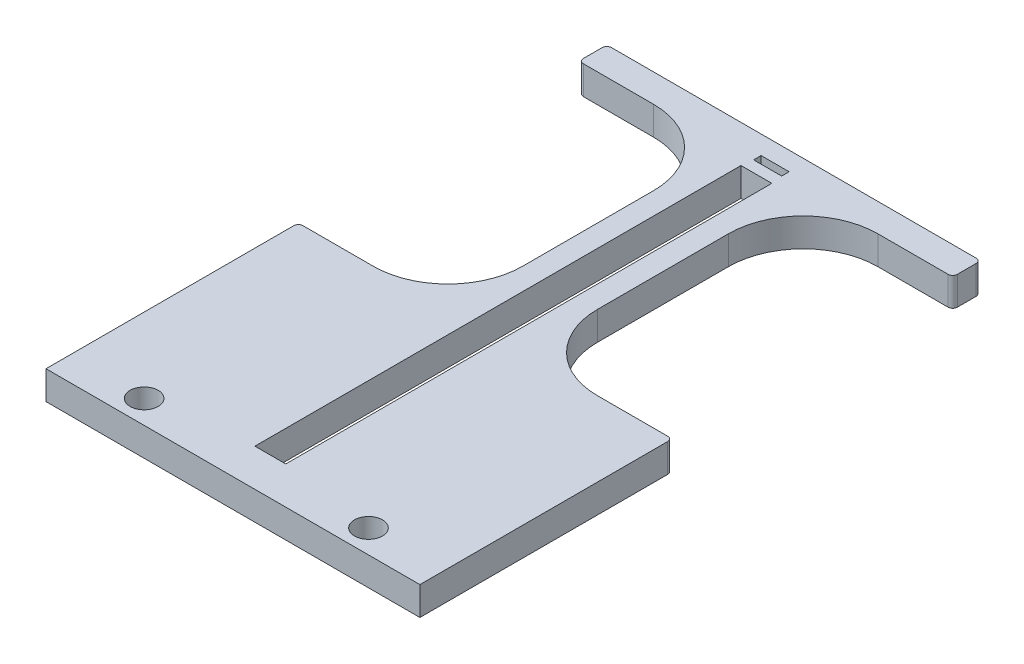
SolidWorks part; units mm, degrees
ref_plane "Front Plane" through (0, 0, 0) normal (0, 0, 1) x (1, 0, 0)
ref_plane "Top Plane" through (0, 0, 0) normal (0, 1, 0) x (1, 0, 0)
ref_plane "Right Plane" through (0, 0, 0) normal (1, 0, 0) x (0, 0, -1)
sketch "Sketch1" plane through (0, 0, 0) normal (0, 1, 0) x (1, 0, 0)
  line L1 (0, 0) -> (40, 0)
  line L2 (0, 0) -> (0, 60)
  line L3 (0, 60) -> (40, 60)
  line L4 (40, 0) -> (40, 60)
  dimension "D1" = 40
  dimension "D2" = 60
extrude "Boss-Extrude1" add sketch "Sketch1" along normal blind 3.05
sketch "Sketch4" plane through (0, 3.05, 0) normal (0, 1, 0) x (1, 0, 0)
  line L0 (20, 60) -> (20, 58)
  line L1 (0, 60) -> (40, 60) construction
  line L3 (21.5, 58) -> (18.5, 58)
  line L4 (18.5, 58) -> (18.5, 57.2)
  line L5 (18.5, 57.2) -> (21.5, 57.2)
  line L6 (21.5, 57.2) -> (21.5, 58)
  line L7 (20, 57.2) -> (20, 56)
  line L9 (21.65, 56) -> (18.35, 56)
  line L10 (18.35, 56) -> (18.35, 4)
  line L11 (18.35, 4) -> (21.65, 4)
  line L12 (21.65, 4) -> (21.65, 56)
  point P10 (20, 58)
  point P22 (20, 56)
  dimension "D1" = 2
  dimension "D2" = 0.8
  dimension "D3" = 1.2
  dimension "D4" = 3
  dimension "D5" = 52
  dimension "D6" = 3.3
extrude "Cut-Extrude1" cut sketch "Sketch4" against normal blind 10 contours L11 L12 L9 L10 | L5 L6 L3 L4
sketch "Sketch5" plane through (0, 3.05, 0) normal (0, 1, 0) x (1, 0, 0)
  line L0 (0, 60) -> (0, 20)
  line L1 (0, 0) -> (0, 60) construction
  line L2 (0, 60) -> (15, 60)
  line L3 (0, 60) -> (40, 60) construction
  line L5 (40, 60) -> (25, 60)
  line L6 (40, 60) -> (40, 20)
  line L7 (40, 0) -> (40, 60) construction
  line L9 (15, 60) -> (15, 20)
  line L10 (15, 20) -> (0, 20)
  line L11 (25, 60) -> (25, 20)
  line L12 (25, 20) -> (40, 20)
  circle A0 centre (7.5, 27.5) radius 7.5
  circle A1 centre (32.5, 27.5) radius 7.5
  line M14 (40, 0) -> (40, 60)
  line M15 (40, 60) -> (0, 60)
  line M16 (0, 60) -> (0, 0)
  dimension "D1" = 40
  dimension "D2" = 15
  dimension "D3" = 40
  dimension "D4" = 15
extrude "Cut-Extrude2" [suppressed] cut sketch "Sketch5" against normal blind 10 contours A0 L9 M15 M16 | A0 | A0 L0 L10 | A1 L6 L11 M15 | A1 | A1 L12 M14
sketch "Sketch6" plane through (0, 3.05, 0) normal (0, 1, 0) x (1, 0, 0)
  line L0 (0, 60) -> (0, 45)
  line L1 (0, 0) -> (0, 60) construction
  line L2 (0, 60) -> (15, 60)
  line L3 (0, 60) -> (40, 60) construction
  line L4 (40, 60) -> (40, 45)
  line L5 (40, 0) -> (40, 60) construction
  line L6 (40, 60) -> (25, 60)
  line L7 (15, 60) -> (0, 45)
  line L8 (25, 60) -> (40, 45)
  dimension "D1" = 15
  dimension "D2" = 15
  dimension "D3" = 15
  dimension "D4" = 15
extrude "Cut-Extrude3" [suppressed] cut sketch "Sketch6" against normal blind 10
sketch "Sketch7" plane through (0, 3.05, 0) normal (0, 1, 0) x (1, 0, 0)
  line L0 (0, 60) -> (0, 57)
  line L1 (0, 0) -> (0, 60) construction
  line L2 (40, 60) -> (40, 57)
  line L3 (0, 57) -> (16, 57)
  line L4 (0, 57) -> (0, 27)
  line L5 (0, 27) -> (16, 27)
  line L6 (16, 57) -> (16, 27)
  line L7 (40, 0) -> (40, 60) construction
  line L9 (40, 57) -> (24, 57)
  line L10 (40, 57) -> (40, 27)
  line L11 (40, 27) -> (24, 27)
  line L12 (24, 57) -> (24, 27)
  circle A0 centre (8, 49) radius 8
  circle A1 centre (8, 35) radius 8
  circle A2 centre (32, 35) radius 8
  circle A3 centre (32, 49) radius 8
  line M18 (40, 0) -> (40, 60)
  line M20 (0, 60) -> (0, 0)
  dimension "D1" = 3
  dimension "D2" = 30
  dimension "D3" = 3
  dimension "D4" = 30
  dimension "D5" = 16
  dimension "D6" = 16
extrude "Cut-Extrude4" cut sketch "Sketch7" against normal blind 10 contours A1 A0 | A0 L3 M20 | A1 L6 A0 | A1 A0 L4 | A1 A0 | A1 L5 M20 | A0 A1 | A3 L12 A2 | A2 A3 | A3 A2 L10 | A2 A3 | A3 A2 | A2 L11 M18 | A3 L9 M18
sketch "Sketch8" plane through (0, 3.05, 0) normal (0, 1, 0) x (1, 0, 0)
  line L0 (0, 0) -> (8, 0)
  line L1 (0, 0) -> (40, 0) construction
  line L2 (8, 0) -> (8, 2.5)
  line L3 (8, 2.5) -> (32, 2.5)
  circle A0 centre (8, 2.5) radius 1.5
  circle A1 centre (32, 2.5) radius 1.5
  dimension "D3" = 3
  dimension "D5" = 3
  dimension "D1" = 8
  dimension "D2" = 2.5
  dimension "D4" = 24
extrude "Cut-Extrude5" cut sketch "Sketch8" against normal blind 10 contours L3 A0 L2 | L2 A0 L3 | A1
fillet "Fillet1" radius 0.5 6 edges at (0, 1.525, -27) (40, 1.525, -27) (40, 1.525, -57) (40, 1.525, -60) (0, 1.525, -60) (0, 1.525, -57)
